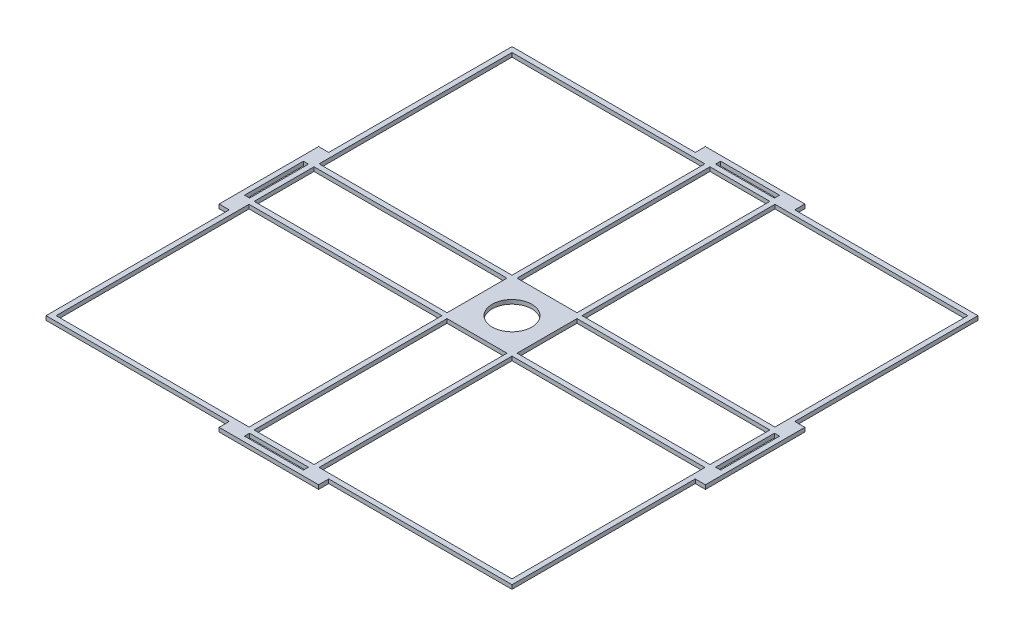
SolidWorks part; units mm, degrees
ref_plane "Front Plane" through (0, 0, 0) normal (0, 0, 1) x (1, 0, 0)
ref_plane "Top Plane" through (0, 0, 0) normal (0, 1, 0) x (1, 0, 0)
ref_plane "Right Plane" through (0, 0, 0) normal (1, 0, 0) x (0, 0, -1)
sketch "Sketch1" plane through (0, 0, 0) normal (0, 1, 0) x (1, 0, 0)
  line L0 (-55, 0) -> (55, 0) construction
  line L1 (-11.225, -11.225) -> (11.225, -11.225)
  line L2 (-11.225, -11.225) -> (-11.225, 11.225)
  line L3 (-11.225, 11.225) -> (11.225, 11.225)
  line L4 (11.225, -11.225) -> (11.225, 11.225)
  line L5 (-11.225, -11.225) -> (11.225, 11.225) construction
  line L6 (-11.225, 11.225) -> (11.225, -11.225) construction
  line L7 (-11.225, 11.225) -> (-1.725, 11.225)
  line L8 (-11.225, 11.225) -> (-11.225, 1.725)
  line L9 (-11.225, 1.725) -> (-1.725, 1.725)
  line L10 (-1.725, 11.225) -> (-1.725, 1.725)
  line L11 (-1.725, -11.225) -> (-1.725, -1.725)
  line L12 (-11.225, -1.725) -> (-1.725, -1.725)
  line L13 (0, -55) -> (0, 55) construction
  line L14 (1.725, -11.225) -> (1.725, -1.725)
  line L15 (11.225, -1.725) -> (1.725, -1.725)
  line L16 (1.725, 11.225) -> (1.725, 1.725)
  line L17 (11.225, 1.725) -> (1.725, 1.725)
  line L18 (-1.475, 1.475) -> (-11.225, 1.475)
  line L19 (11.475, -11.475) -> (-11.475, -11.475)
  line L20 (11.475, -11.475) -> (11.475, 11.475)
  line L21 (11.475, 11.475) -> (-11.475, 11.475)
  line L22 (-11.475, -11.475) -> (-11.475, 11.475)
  line L23 (11.475, -11.475) -> (-11.475, 11.475) construction
  line L24 (11.475, 11.475) -> (-11.475, -11.475) construction
  line L25 (11.225, -1.475) -> (1.475, -1.475)
  line L26 (11.225, -1.475) -> (11.225, 1.475)
  line L27 (11.225, 1.475) -> (1.475, 1.475)
  line L28 (-11.225, -1.475) -> (-11.225, 1.475)
  line L29 (11.225, -1.475) -> (-11.225, 1.475) construction
  line L30 (11.225, 1.475) -> (-11.225, -1.475) construction
  line L31 (-1.475, -11.225) -> (1.475, -11.225)
  line L32 (-1.475, -11.225) -> (-1.475, -1.475)
  line L33 (-1.475, 11.225) -> (1.475, 11.225)
  line L34 (1.475, -11.225) -> (1.475, -1.475)
  line L35 (-1.475, -11.225) -> (1.475, 11.225) construction
  line L36 (-1.475, 11.225) -> (1.475, -11.225) construction
  line L37 (-1.475, 1.475) -> (-1.475, 11.225)
  line L38 (-1.475, -1.475) -> (-11.225, -1.475)
  line L39 (1.475, 1.475) -> (1.475, 11.225)
  line L40 (-11.475, 0) -> (-15.585, 0) construction
  line L41 (1.725, 1.725) -> (-1.725, 1.725)
  line L42 (1.725, 1.725) -> (1.725, -1.725)
  line L43 (1.725, -1.725) -> (-1.725, -1.725)
  line L44 (-1.725, 1.725) -> (-1.725, -1.725)
  line L45 (1.725, 1.725) -> (-1.725, -1.725) construction
  line L46 (1.725, -1.725) -> (-1.725, 1.725) construction
  line L47 (-11.475, -2.45) -> (-11.725, -2.45)
  line L48 (-11.475, 1.45) -> (-11.725, 1.45)
  line L49 (-11.475, 1.45) -> (-11.475, 2.45)
  line L50 (-11.475, 2.45) -> (-11.725, 2.45)
  line L51 (-11.725, 1.45) -> (-11.725, 2.45)
  line L52 (-11.725, -1.45) -> (-11.725, -2.45)
  line L53 (-11.475, -1.45) -> (-11.725, -1.45)
  line L54 (-11.475, -1.45) -> (-11.475, -2.45)
  line L55 (1.45, 11.475) -> (2.45, 11.475)
  line L56 (1.45, 11.475) -> (1.45, 11.725)
  line L57 (1.45, 11.725) -> (2.45, 11.725)
  line L58 (2.45, 11.475) -> (2.45, 11.725)
  line L59 (-2.45, 11.475) -> (-2.45, 11.725)
  line L60 (-1.45, 11.725) -> (-2.45, 11.725)
  line L61 (-1.45, 11.475) -> (-1.45, 11.725)
  line L62 (-1.45, 11.475) -> (-2.45, 11.475)
  line L63 (11.475, -1.45) -> (11.475, -2.45)
  line L64 (11.475, -1.45) -> (11.725, -1.45)
  line L65 (11.725, -1.45) -> (11.725, -2.45)
  line L66 (11.475, -2.45) -> (11.725, -2.45)
  line L67 (11.475, 2.45) -> (11.725, 2.45)
  line L68 (11.725, 1.45) -> (11.725, 2.45)
  line L69 (11.475, 1.45) -> (11.725, 1.45)
  line L70 (11.475, 1.45) -> (11.475, 2.45)
  line L71 (-1.45, -11.475) -> (-2.45, -11.475)
  line L72 (-1.45, -11.475) -> (-1.45, -11.725)
  line L73 (-1.45, -11.725) -> (-2.45, -11.725)
  line L74 (-2.45, -11.475) -> (-2.45, -11.725)
  line L75 (2.45, -11.475) -> (2.45, -11.725)
  line L76 (1.45, -11.725) -> (2.45, -11.725)
  line L77 (1.45, -11.475) -> (1.45, -11.725)
  line L78 (1.45, -11.475) -> (2.45, -11.475)
  line L79 (2.45, 11.725) -> (-2.45, 11.725)
  line L80 (-11.725, 2.45) -> (-11.975, 2.45)
  line L81 (-11.725, 2.45) -> (-11.725, -2.45)
  line L82 (-11.725, -2.45) -> (-11.975, -2.45)
  line L83 (-11.975, 2.45) -> (-11.975, -2.45)
  line L84 (2.45, 11.725) -> (2.45, 11.975)
  line L85 (2.45, 11.975) -> (-2.45, 11.975)
  line L86 (-2.45, 11.725) -> (-2.45, 11.975)
  line L87 (11.725, -2.45) -> (11.725, 2.45)
  line L88 (11.725, -2.45) -> (11.975, -2.45)
  line L89 (11.975, -2.45) -> (11.975, 2.45)
  line L90 (11.725, 2.45) -> (11.975, 2.45)
  line L91 (-2.45, -11.725) -> (2.45, -11.725)
  line L92 (-2.45, -11.725) -> (-2.45, -11.975)
  line L93 (-2.45, -11.975) -> (2.45, -11.975)
  line L94 (2.45, -11.725) -> (2.45, -11.975)
  circle A0 centre (0, 0) radius 0.975
  point P0 (0, 0)
  point P77 (0, 0)
  point P92 (0, 0)
  dimension "D3" = 1.95
  dimension "D1" = 22.45
  dimension "D2" = 9.5
  dimension "D4" = 0.25
  dimension "D5" = 0.25
  dimension "D6" = 0.25
  dimension "D7" = 0.25
  dimension "D8" = 0.25
  dimension "D9" = 1.45
  dimension "D10" = 1
  dimension "D12" = 0.25
  dimension "D11" = 4
  dimension "D13" = 4
extrude "Boss-Extrude5" add sketch "Sketch1" along normal blind 0.2 contours L22 L19 L20 L21 L4 L1 L2 L3 | L32 L43 L11 L1 | L44 L38 L2 L12 | L18 L44 L38 L32 L43 L34 L25 L42 L27 L39 L41 L37 A0 | L38 L44 L43 L32 | L43 L42 L25 L34 | L25 L42 L15 L4 | L14 L43 L34 L1 | L42 L41 L39 L27 | L17 L42 L27 L4 | L41 L16 L3 L39 | L41 L44 L18 L37 | L44 L9 L2 L18 | L41 L37 L3 L10 | L22 L53 L52 L47 | L51 L48 L22 L50 | L20 L66 L65 L64 | L20 L69 L68 L67 | L19 L77 L76 L75 | L19 L74 L73 L72 | L21 L58 L57 L56 | L21 L61 L60 L59 | L80 L83 L82 L52 L81 L51 | L94 L76 L91 L73 L92 L93 | L90 L68 L87 L65 L88 L89 | L86 L60 L79 L57 L84 L85
